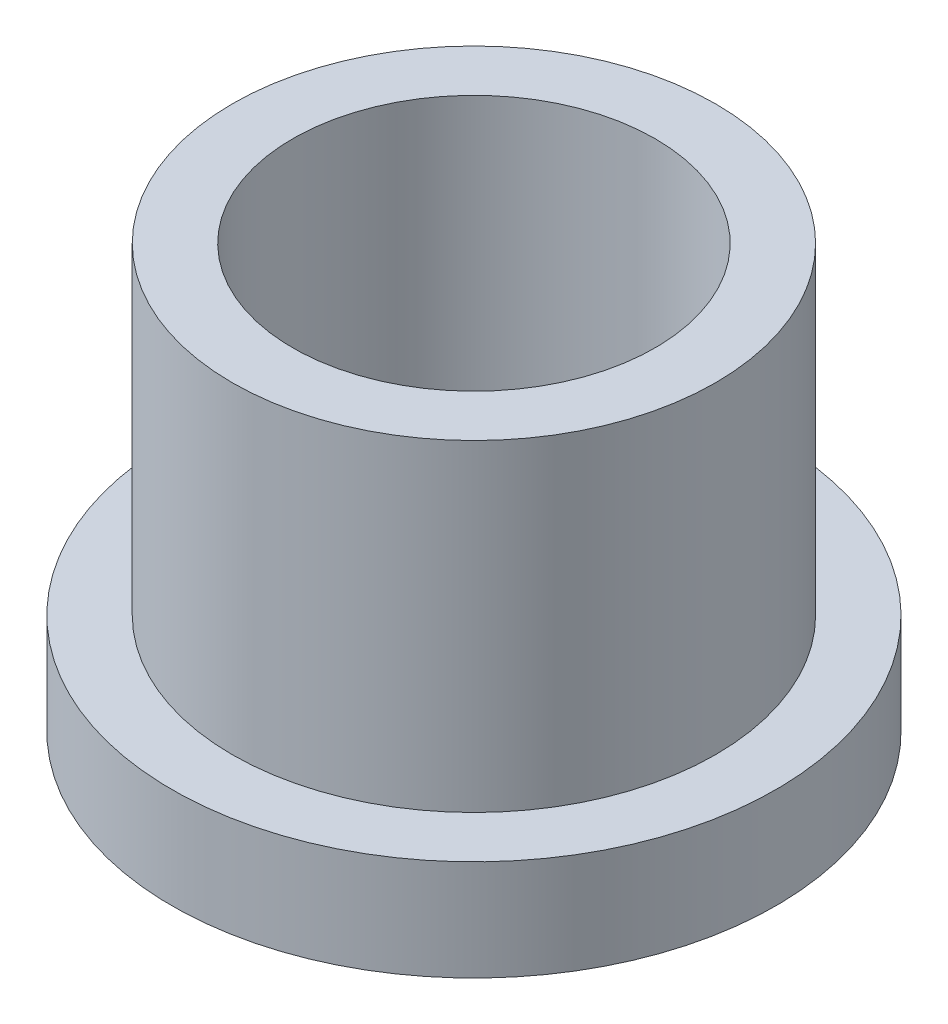
SolidWorks part; units mm, degrees
ref_plane "Front Plane" through (0, 0, 0) normal (0, 0, 1) x (1, 0, 0)
ref_plane "Top Plane" through (0, 0, 0) normal (0, 1, 0) x (1, 0, 0)
ref_plane "Right Plane" through (0, 0, 0) normal (1, 0, 0) x (0, 0, -1)
sketch "Sketch1" plane through (0, 0, 0) normal (0, 0, 1) x (1, 0, 0)
  line L0 (9, 0) -> (9, 21)
  line L1 (9, 21) -> (12, 21)
  line L2 (12, 21) -> (12, 5)
  line L3 (12, 5) -> (15, 5)
  line L4 (15, 5) -> (15, 0)
  line L5 (15, 0) -> (9, 0)
  line L6 (0, 0) -> (0, 21) construction
  dimension "D1" = 9
  dimension "D2" = 21
  dimension "D3" = 16
  dimension "D4" = 15
  dimension "D5" = 12
revolve "Revolve1" add sketch "Sketch1" angle 360 about L6
